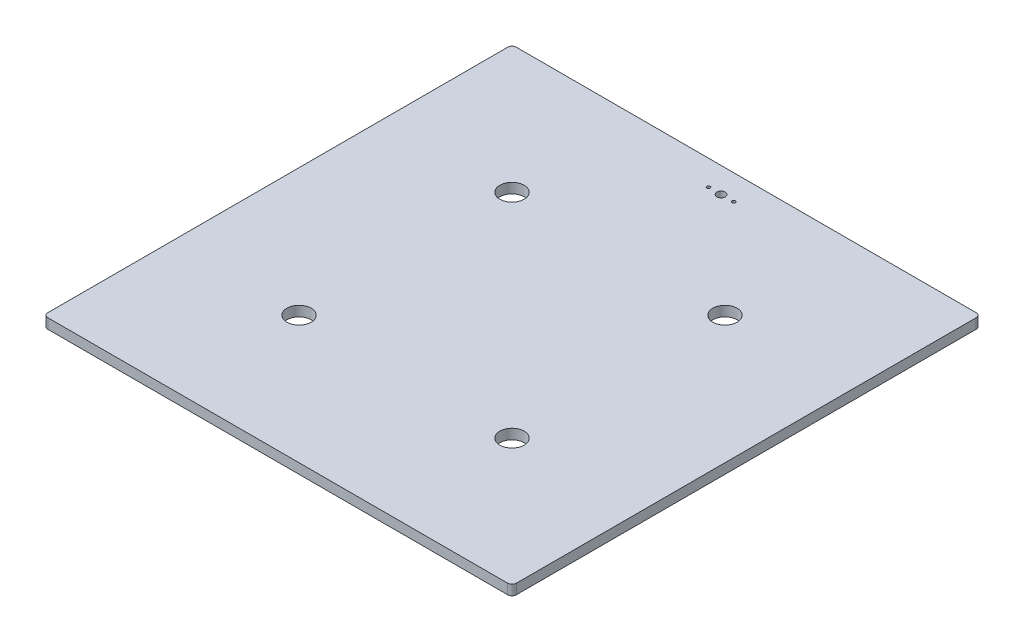
SolidWorks part; units mm, degrees
ref_plane "Front Plane" through (0, 0, 0) normal (0, 0, 1) x (1, 0, 0)
ref_plane "Top Plane" through (0, 0, 0) normal (0, 1, 0) x (1, 0, 0)
ref_plane "Right Plane" through (0, 0, 0) normal (1, 0, 0) x (0, 0, -1)
sketch "Sketch1" plane through (0, 0, 0) normal (0, 1, 0) x (1, 0, 0)
  line L1 (-139.7, -139.7) -> (139.7, -139.7)
  line L2 (-139.7, -139.7) -> (-139.7, 139.7)
  line L3 (-139.7, 139.7) -> (139.7, 139.7)
  line L4 (139.7, -139.7) -> (139.7, 139.7)
  line L5 (-139.7, -139.7) -> (139.7, 139.7) construction
  line L6 (-139.7, 139.7) -> (139.7, -139.7) construction
  point P0 (0, 0)
  dimension "D1" = 279.4
  dimension "D2" = 279.4
extrude "Boss-Extrude1" add sketch "Sketch1" along normal blind 5.9944
sketch "Sketch2" plane through (0, 5.9944, 0) normal (0, 1, 0) x (1, 0, 0)
  line L1 (-63.5, -63.5) -> (63.5, -63.5) construction
  line L2 (-63.5, -63.5) -> (-63.5, 63.5) construction
  line L3 (-63.5, 63.5) -> (63.5, 63.5) construction
  line L4 (63.5, -63.5) -> (63.5, 63.5) construction
  line L5 (-63.5, -63.5) -> (63.5, 63.5) construction
  line L6 (-63.5, 63.5) -> (63.5, -63.5) construction
  circle A0 centre (-63.5, 63.5) radius 7.25
  circle A1 centre (63.5, 63.5) radius 7.25
  circle A2 centre (63.5, -63.5) radius 7.25
  circle A3 centre (-63.5, -63.5) radius 7.25
  point P0 (0, 0)
  dimension "D3" = 14.5
  dimension "D4" = 14.5
  dimension "D5" = 14.5
  dimension "D6" = 14.5
  dimension "D1" = 127
  dimension "D2" = 127
extrude "Cut-Extrude1" cut sketch "Sketch2" against normal through all
fillet "Fillet1" radius 2.54 4 edges at (-139.7, 2.9972, 139.7) (139.7, 2.9972, 139.7) (139.7, 2.9972, -139.7) (-139.7, 2.9972, -139.7)
sketch "Sketch3" plane through (0, 5.9944, 0) normal (0, 1, 0) x (1, 0, 0)
  line L0 (-7.5, 124.7) -> (7.5, 124.7)
  line L1 (137.16, 139.7) -> (-137.16, 139.7) construction
  circle A0 centre (0, 124.7) radius 2.5
  circle A1 centre (7.5, 124.7) radius 1
  circle A2 centre (-7.5, 124.7) radius 1
  point P5 (0, 124.7)
  dimension "D1" = 5
  dimension "D2" = 2
  dimension "D3" = 2
  dimension "D4" = 15
  dimension "D5" = 15
extrude "Cut-Extrude2" cut sketch "Sketch3" against normal through all contours L0 A0 | L0 A0 | A1 | A2
